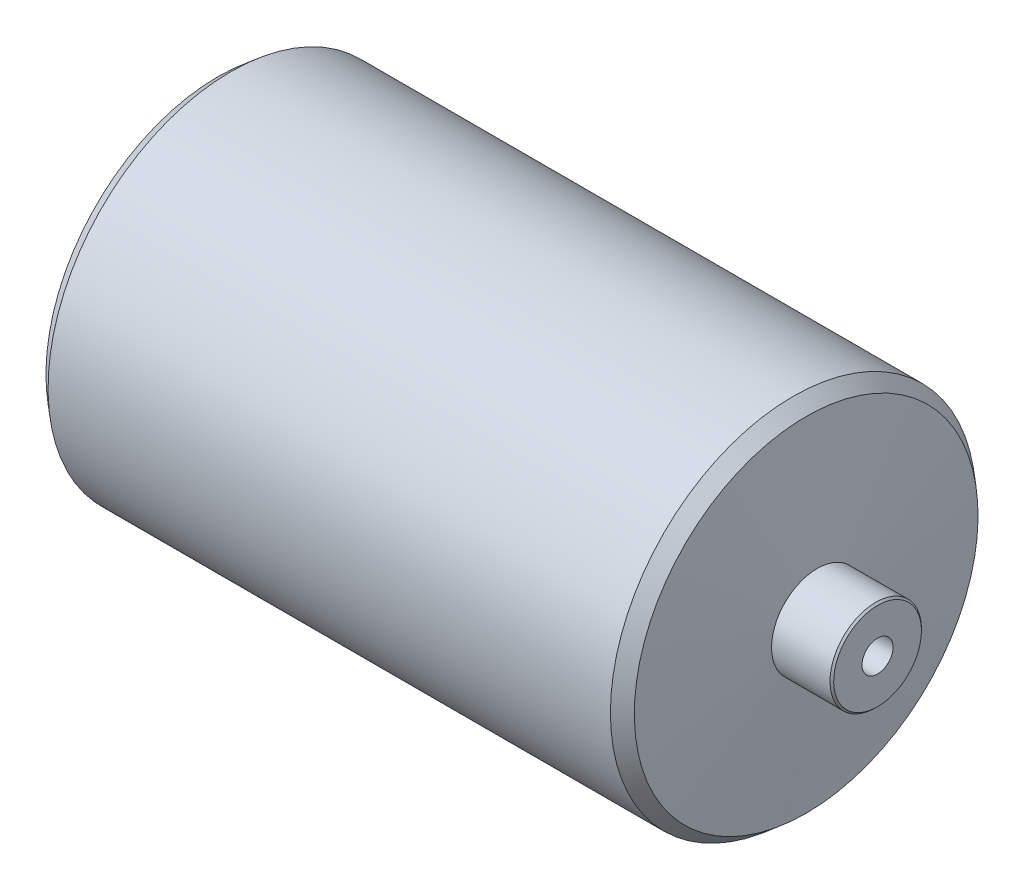
SolidWorks part; units mm, degrees
ref_plane "Alzado" through (0, 0, 0) normal (0, 0, 1) x (1, 0, 0)
ref_plane "Planta" through (0, 0, 0) normal (0, 1, 0) x (1, 0, 0)
ref_plane "Vista lateral" through (0, 0, 0) normal (1, 0, 0) x (0, 0, -1)
sketch "Croquis1" plane through (0, 0, 0) normal (0, 0, 1) x (1, 0, 0)
  line L0 (0, 0) -> (0, 12)
  line L1 (0.5, 12.5) -> (16.5, 12.5)
  line L2 (16.5, 12.5) -> (19.5194, 47.0114)
  line L4 (23.081, 50) -> (176.919, 50)
  line L5 (100, 50) -> (100, 0) construction
  line L6 (200, 0) -> (0, 0)
  line L7 (0, 12) -> (0.5, 12.5)
  line L8 (19.5194, 47.0114) -> (23.081, 50)
  line L9 (180.4806, 47.0114) -> (176.919, 50)
  line L10 (200, 12) -> (199.5, 12.5)
  line L11 (183.5, 12.5) -> (180.4806, 47.0114)
  line L12 (199.5, 12.5) -> (183.5, 12.5)
  line L13 (200, 0) -> (200, 12)
  point P1 (0, 12.5)
  point P5 (19.7808, 50)
  point P13 (180.2192, 50)
  point P14 (200, 12.5)
  dimension "D1" = 100
  dimension "D2" = 12.5
  dimension "D3" = 85
  dimension "D4" = 50
  dimension "D5" = 16.5
  dimension "D6" = 0.5
  dimension "D7" = 45
  dimension "D8" = 3
  dimension "D9" = 45
revolve "Revolución1" add sketch "Croquis1" angle 360 about L6
sketch "Croquis2" plane through (200, 0, 0) normal (1, 0, 0) x (0, 0, -1)
  circle A1 centre (0, 0) radius 12
  circle A2 centre (0, 0) radius 12
  dimension "D1" = 0
sketch "Croquis3" plane through (0, 0, 0) normal (-1, 0, 0) x (0, 0, 1)
  circle A1 centre (0, 0) radius 12
  circle A2 centre (0, 0) radius 12
  dimension "D1" = 0
hole_wizard "Taladro roscado M101" positions "Croquis3D1" profile "Croquis4" tap size "M10" standard "ISO"
sketch3d "Croquis3D1"
  point P0 (200, 0, 0)
  point P3 (0, 0, 0)
sketch "Croquis4" plane through (200, 0, 0) normal (0, 1, 0) x (0, 0, -1)
  line L0 (0, 0) -> (0, 59)
  line L1 (0, 59) -> (4.25, 56.4463)
  line L2 (4.25, 56.4463) -> (4.25, 0)
  line L5 (4.25, 0) -> (0, 0)
  line L10 (0, 59) -> (-4.25, 56.4463) construction
  line L11 (0, -6.35) -> (0, 107.95) construction
  dimension "Diámetro de perforador para roscar" = 8.5
  dimension "Profundidad de perforador para roscar" = 59
  dimension "Ángulo de perforador" = 118
hole_wizard "Taladro roscado M102" positions "Croquis3D2" profile "Croquis5" tap size "M10" standard "ISO"
sketch3d "Croquis3D2"
  point P0 (0, 0, 0)
  point P3 (0, 0, 0)
  point P6 (0, 0, 0)
sketch "Croquis5" plane through (0, 0, 0) normal (0, 1, 0) x (0, 0, 1)
  line L0 (0, 0) -> (0, 59)
  line L1 (0, 59) -> (4.25, 56.4463)
  line L2 (4.25, 56.4463) -> (4.25, 0)
  line L5 (4.25, 0) -> (0, 0)
  line L10 (0, 59) -> (-4.25, 56.4463) construction
  line L11 (0, -6.35) -> (0, 107.95) construction
  dimension "Diámetro de perforador para roscar" = 8.5
  dimension "Profundidad de perforador para roscar" = 59
  dimension "Ángulo de perforador" = 118
